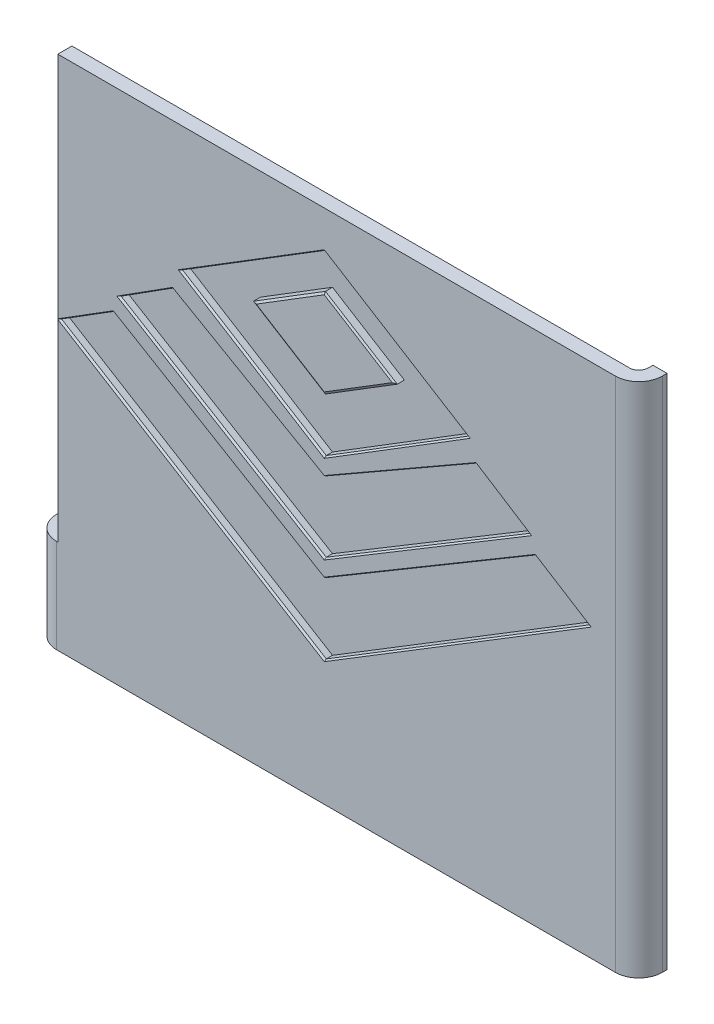
SolidWorks part; units mm, degrees
ref_plane "Front Plane" through (0, 0, 0) normal (0, 0, 1) x (1, 0, 0)
ref_plane "Top Plane" through (0, 0, 0) normal (0, 1, 0) x (1, 0, 0)
ref_plane "Right Plane" through (0, 0, 0) normal (1, 0, 0) x (0, 0, -1)
sketch "Sketch1" plane through (0, 0, 0) normal (0, 0, 1) x (1, 0, 0)
  line L0 (0, -3.575) -> (0, 3.575) construction
  line L1 (-69.5, 56) -> (59.5, 56)
  line L2 (-69.5, 56) -> (-69.5, -54)
  line L3 (-69.5, -54) -> (59.5, -54)
  line L4 (59.5, 56) -> (59.5, -54)
  line L5 (3.575, 0) -> (-3.575, 0) construction
  dimension "D1" = 59.5
  dimension "D2" = 69.5
  dimension "D3" = 56
  dimension "D4" = 54
extrude "Boss-Extrude1" add sketch "Sketch1" along normal blind 3
sketch "Sketch8" plane through (0, 0, 0) normal (0, 0, -1) x (-1, 0, 0)
  line L0 (69.5, -54) -> (-59.5, -54) construction
  line L1 (-59.5, 56) -> (-56.5, 56)
  line L2 (-59.5, 56) -> (-59.5, -54)
  line L3 (-59.5, -54) -> (-56.5, -54)
  line L4 (-56.5, 56) -> (-56.5, -54)
  dimension "D1" = 3
extrude "Boss-Extrude5" add sketch "Sketch8" along normal blind 3
fillet "Fillet4" radius 2 1 edges at (56.5, 1, 0)
fillet "Fillet5" radius 5 1 edges at (59.5, 1, 3)
sketch "Sketch9" plane through (0, 0, -3) normal (0, 0, -1) x (-1, 0, 0)
  line L0 (-56.5, 56) -> (-59.5, 56) construction
  line L1 (-58.5, 56) -> (-57.5, 56)
  line L2 (-58.5, 56) -> (-58.5, -54)
  line L3 (-58.5, -54) -> (-57.5, -54)
  line L4 (-57.5, 56) -> (-57.5, -54)
  line L5 (-59.5, -54) -> (-56.5, -54) construction
  line L6 (-59.5, 56) -> (-59.5, -54) construction
  line L7 (-56.5, -54) -> (-56.5, 56) construction
  dimension "D1" = 1
  dimension "D2" = 1
extrude "Boss-Extrude6" add sketch "Sketch9" along normal blind 2.5
sketch "Sketch10" plane through (0, 56, 0) normal (0, 1, 0) x (1, 0, 0)
  line L0 (57.5, 5.5) -> (57, 3)
  line L1 (56.5, 3) -> (57.5, 3) construction
  line L2 (57, 3) -> (57.5, 3)
  line L3 (57.5, 3) -> (57.5, 5.5)
extrude "Boss-Extrude7" add sketch "Sketch10" against normal through all
sketch "Sketch13" plane through (0, 0, 3) normal (0, 0, 1) x (1, 0, 0)
  line L0 (-7.5, 56) -> (-7.5, -54) construction
  line L1 (54.5, 56) -> (-69.5, 56) construction
  line L2 (-69.5, -54) -> (54.5, -54) construction
  line L3 (-7.5, 48) -> (-38.1127, 29.0563)
  line L4 (-69.5, 56) -> (-69.5, -54) construction
  line L5 (-69.5, 1) -> (59.5, 1) construction
  line L6 (59.5, 56) -> (59.5, -54) construction
  line L7 (-38.1127, 29.0563) -> (-7.5, 10.1126)
  line L8 (-7.5, 10.1126) -> (23.1127, 29.0563)
  line L9 (23.1127, 29.0563) -> (-7.5, 48)
  line L10 (-7.5, 40.5) -> (-22.8063, 31.0281)
  line L11 (-22.8063, 31.0281) -> (-7.5, 21.5563)
  line L12 (-7.5, 21.5563) -> (7.8063, 31.0281)
  line L13 (7.8063, 31.0281) -> (-7.5, 40.5)
  line L14 (-39.807, 24.905) -> (-51.1977, 17.6592)
  line L15 (-51.1977, 17.6592) -> (-7.5, -8.6374)
  line L16 (-7.5, -8.6374) -> (36.1977, 17.6592)
  line L17 (36.1977, 17.6592) -> (24.807, 24.905)
  line L18 (24.807, 24.905) -> (-7.5, 6.3626)
  line L19 (-7.5, 6.3626) -> (-39.807, 24.905)
  line L20 (-52.4314, 14.2815) -> (-63.8765, 7.122)
  line L21 (-63.8765, 7.122) -> (-7.5, -27.3874)
  line L22 (-7.5, -27.3874) -> (48.8765, 7.122)
  line L23 (48.8765, 7.122) -> (37.4314, 14.2815)
  line L24 (37.4314, 14.2815) -> (-7.5, -12.3874)
  line L25 (-7.5, -12.3874) -> (-52.4314, 14.2815)
  dimension "D1" = 36
  dimension "D2" = 36
  dimension "D3" = 36
  dimension "D4" = 36
  dimension "D5" = 63.5
  dimension "D6" = 18
  dimension "D7" = 18
  dimension "D8" = 18
  dimension "D9" = 18
  dimension "D10" = 63.5
  dimension "D11" = 7.5
  dimension "D12" = 63.5
  dimension "D13" = 13.5
  dimension "D14" = 15
  dimension "D15" = 3.75
  dimension "D16" = 8
  dimension "D17" = 37.25
  dimension "D18" = 51
  dimension "D19" = 51
  dimension "D20" = 37.25
  dimension "D21" = 52.25
  dimension "63.5" = 63.5
  dimension "D22" = 13.5
  dimension "D23" = 15
  dimension "D24" = 3.75
  dimension "D25" = 52.25
  dimension "D26" = 66.1
  dimension "D27" = 66.1
extrude "Cut-Extrude3" cut sketch "Sketch13" against normal blind 1.75
chamfer "Chamfer3" distance 0.25 angle 60 20 edges at (-15.1532, 35.7641, 3) (0.1532, 35.7641, 3) (0.1532, 26.2922, 3) (-15.1532, 26.2922, 3) (20.6883, -10.1327, 3) (43.154, 10.7018, 3) (14.9657, 0.9471, 3) (-29.9657, 0.9471, 3) (-58.154, 10.7018, 3) (-35.6883, -10.1327, 3) (8.6535, 15.6338, 3) (30.5023, 21.2821, 3) (14.3488, 4.5109, 3) (-29.3488, 4.5109, 3) (-45.5023, 21.2821, 3) (-23.6535, 15.6338, 3) (-22.8063, 19.5844, 3) (7.8063, 19.5844, 3) (7.8063, 38.5281, 3) (-22.8063, 38.5281, 3)
sketch "Sketch14" plane through (0, 0, 0) normal (0, 0, -1) x (-1, 0, 0)
  line L0 (69.5, -54) -> (-54.5, -54) construction
  line L1 (69.5, 56) -> (66.24, 56)
  line L2 (69.5, 56) -> (69.5, -54)
  line L3 (69.5, -54) -> (66.24, -54)
  line L4 (66.24, 56) -> (66.24, -54)
  dimension "D1" = 3.26
extrude "Boss-Extrude8" add sketch "Sketch14" along normal blind 3.5
fillet "Fillet6" radius 2 1 edges at (-66.24, 1, 0)
fillet "Fillet7" radius 5 1 edges at (-69.5, 1, 3)
sketch "Sketch17" plane through (0, 0, -3.5) normal (0, 0, -1) x (-1, 0, 0)
  line L1 (69.5, 56) -> (64.25, 56)
  line L2 (69.5, 56) -> (69.5, -34)
  line L3 (69.5, -34) -> (64.25, -34)
  line L4 (64.25, 56) -> (64.25, -34)
  dimension "D1" = 5.25
  dimension "D2" = 90
extrude "Cut-Extrude4" cut sketch "Sketch17" against normal up to surface (6.5 mm away)
sketch "Sketch18" plane through (0, 56, 0) normal (0, 1, 0) x (1, 0, 0)
  line L1 (59.5, 3) -> (56.5, 3)
  line L2 (59.5, 3) -> (59.5, 6.302)
  line L3 (59.5, 6.302) -> (56.5, 6.302)
  line L4 (56.5, 3) -> (56.5, 6.302)
extrude "Cut-Extrude5" cut sketch "Sketch18" against normal up to surface (110 mm away) up to face at (10.7675, -54, -1.8188)
